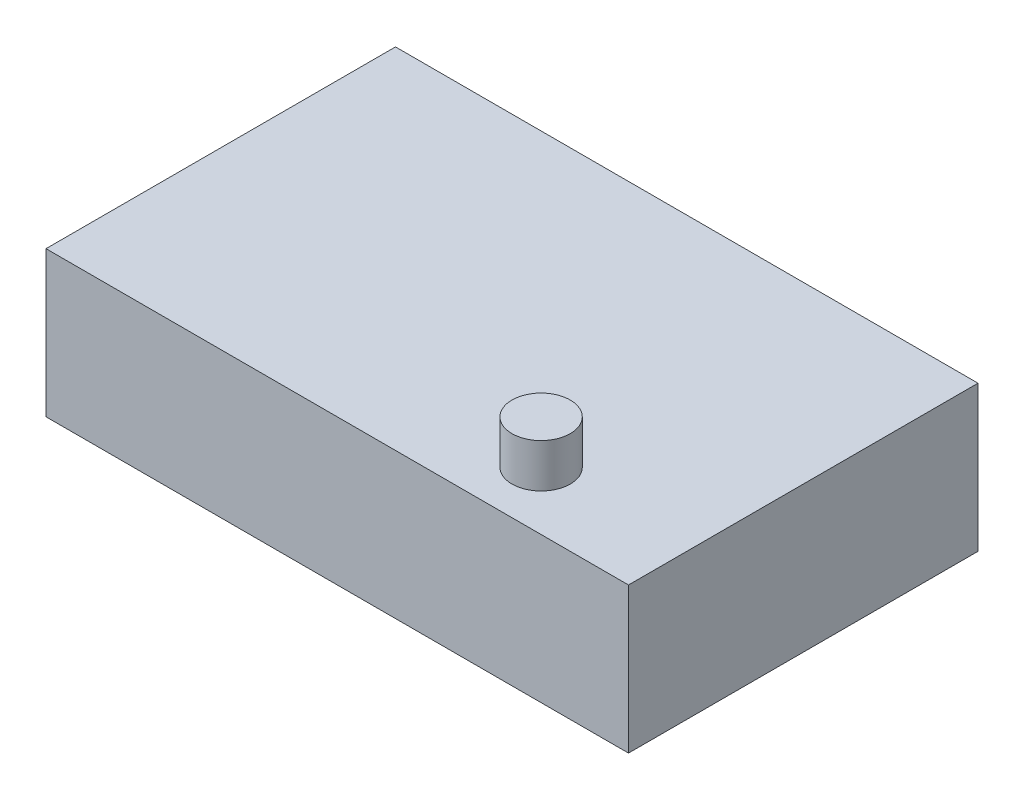
SolidWorks part; units mm, degrees
ref_plane "Front Plane" through (0, 0, 0) normal (0, 0, 1) x (1, 0, 0)
ref_plane "Top Plane" through (0, 0, 0) normal (0, 1, 0) x (1, 0, 0)
ref_plane "Right Plane" through (0, 0, 0) normal (1, 0, 0) x (0, 0, -1)
sketch "Sketch1" plane through (0, 0, 0) normal (0, 1, 0) x (1, 0, 0)
  line L1 (10, -6) -> (-10, -6)
  line L2 (10, -6) -> (10, 6)
  line L3 (10, 6) -> (-10, 6)
  line L4 (-10, -6) -> (-10, 6)
  line L5 (10, -6) -> (-10, 6) construction
  line L6 (10, 6) -> (-10, -6) construction
  point P0 (0, 0)
  dimension "D1" = 20
  dimension "D2" = 12
extrude "Boss-Extrude1" add sketch "Sketch1" along normal blind 5
ref_plane "Plane1" through (0, 5, 0) normal (0, 1, 0) x (1, 0, 0)
sketch "Sketch2" plane through (0, 5, 0) normal (0, 1, 0) x (1, 0, 0)
  line L0 (10, 6) -> (-10, 6) construction
  circle A0 centre (5, -4) radius 1
  dimension "D2" = 2
  dimension "D1" = 10
extrude "Boss-Extrude2" add sketch "Sketch2" along normal blind 1.5
